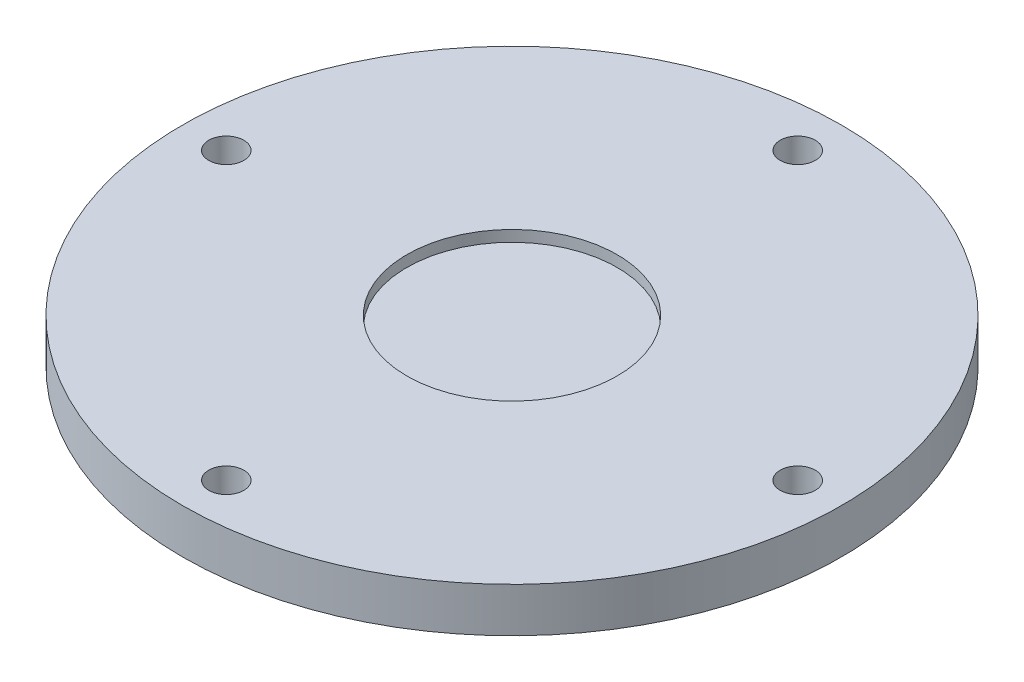
SolidWorks part; units mm, degrees
material "AISI 1045 Steel, cold drawn"
ref_plane "Frontal Plane" through (0, 0, 0) normal (0, 0, 1) x (1, 0, 0)
ref_plane "Horizontal Plane" through (0, 0, 0) normal (0, 1, 0) x (1, 0, 0)
ref_plane "Profile Plane" through (0, 0, 0) normal (1, 0, 0) x (0, 0, -1)
sketch "Sketch1" plane through (0, 0, 0) normal (0, 1, 0) x (1, 0, 0)
  circle A0 centre (0, 0) radius 47
  circle A1 centre (0, 40.75) radius 2.5
  circle A2 centre (40.75, 0) radius 2.5
  circle A3 centre (0, -40.75) radius 2.5
  circle A4 centre (-40.75, 0) radius 2.5
  circle A5 centre (0, 0) radius 40.75 construction
  dimension "D1" = 94
  dimension "D3" = 5
  dimension "D2" = 81.5
  dimension "D4" = 4
extrude "Boss-Extrude1" add sketch "Sketch1" along normal blind 6.35
sketch "Sketch2" plane through (0, 6.35, 0) normal (0, 1, 0) x (1, 0, 0)
  circle A0 centre (0, 0) radius 15
  dimension "D1" = 30
extrude "Cut-Extrude1" cut sketch "Sketch2" against normal blind 1.5875
